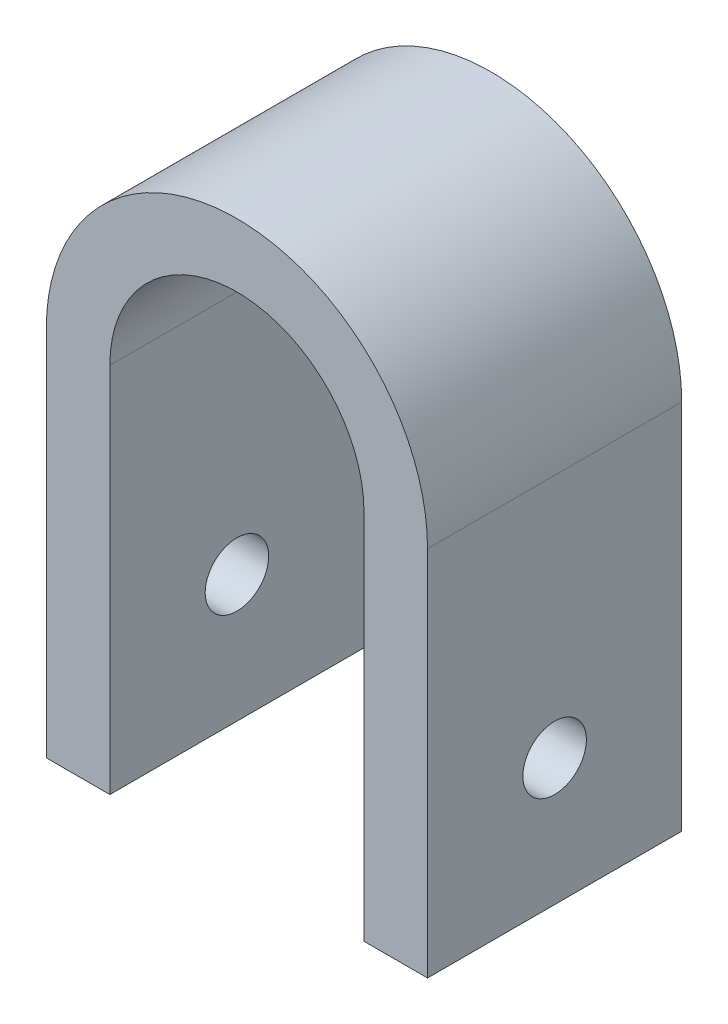
SolidWorks part; units mm, degrees
ref_plane "Front Plane" through (0, 0, 0) normal (0, 0, 1) x (1, 0, 0)
ref_plane "Top Plane" through (0, 0, 0) normal (0, 1, 0) x (1, 0, 0)
ref_plane "Right Plane" through (0, 0, 0) normal (1, 0, 0) x (0, 0, -1)
sketch "Sketch1" plane through (0, 0, 0) normal (0, 0, 1) x (1, 0, 0)
  line L0 (-4, 0) -> (-4, -11.7015)
  line L1 (-4, -1.0579) -> (-4, -25) construction
  line L3 (4, -21.6) -> (4, -1.0579) construction
  line L4 (-6, 0) -> (-6, -11.7015)
  line L5 (-6, -11.7015) -> (-4, -11.7015)
  line L6 (4, 0) -> (4, -11.7015)
  line L7 (6, 0) -> (6, -11.7015)
  line L8 (6, -11.7015) -> (4, -11.7015)
  arc A0 (4, 0) -> (-4, 0) centre (0, 0) ccw
  arc A1 (6, 0) -> (-6, 0) centre (0, 0) ccw
  dimension "D2" = 12
extrude "Boss-Extrude1" add sketch "Sketch1" along normal blind 8
sketch "Sketch2" plane through (-6, 0, 0) normal (-1, 0, 0) x (0, 0, 1)
  line L0 (0, -11.7015) -> (4, -7.7015) construction
  line L1 (4, -7.7015) -> (8, -11.7015) construction
  line L2 (8, -11.7015) -> (0, -11.7015) construction
  circle A0 centre (4, -7.7015) radius 1
  dimension "D2" = 2
  dimension "D1" = 4
extrude "Cut-Extrude1" cut sketch "Sketch2" against normal through all
